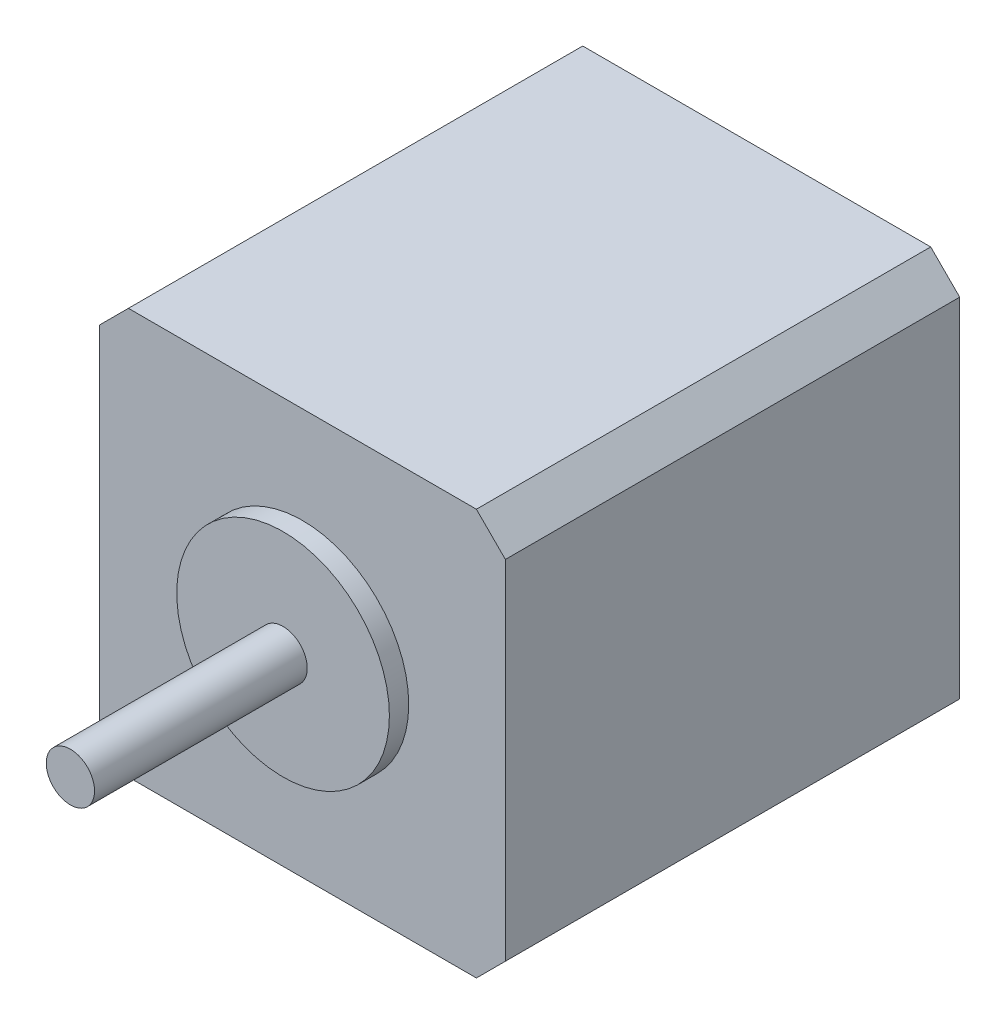
SolidWorks part; units mm, degrees
ref_plane "前视基准面" through (0, 0, 0) normal (0, 0, 1) x (1, 0, 0)
ref_plane "上视基准面" through (0, 0, 0) normal (0, 1, 0) x (1, 0, 0)
ref_plane "右视基准面" through (0, 0, 0) normal (1, 0, 0) x (0, 0, -1)
sketch "草图1" plane through (0, 0, 0) normal (0, 0, 1) x (1, 0, 0)
  line L1 (0, 0) -> (-42, 0)
  line L2 (0, 0) -> (0, 42)
  line L3 (0, 42) -> (-42, 42)
  line L4 (-42, 0) -> (-42, 42)
  dimension "D1" = 42
  dimension "D2" = 42
extrude "凸台-拉伸1" add sketch "草图1" along normal blind 47
chamfer "倒角1" distance 3 angle 45 4 edges at (-42, 0, 23.5) (0, 0, 23.5) (-42, 42, 23.5) (0, 42, 23.5)
sketch "草图2" plane through (0, 0, 47) normal (0, 0, 1) x (1, 0, 0)
  line L0 (-21, 42) -> (-21, 0) construction
  line L1 (-3, 42) -> (-39, 42) construction
  line L2 (-39, 0) -> (-3, 0) construction
  line L3 (-42, 21) -> (-21, 21) construction
  line L4 (-42, 39) -> (-42, 3) construction
  circle A0 centre (-21, 21) radius 11
  point P4 (-21, 42)
  point P7 (-21, 0)
  point P12 (-42, 21)
  dimension "D1" = 22
extrude "凸台-拉伸2" add sketch "草图2" along normal blind 2
sketch "草图3" plane through (0, 0, 49) normal (0, 0, 1) x (1, 0, 0)
  circle A0 centre (-21, 21) radius 2.5
  dimension "D1" = 5
extrude "凸台-拉伸3" add sketch "草图3" along normal blind 22
